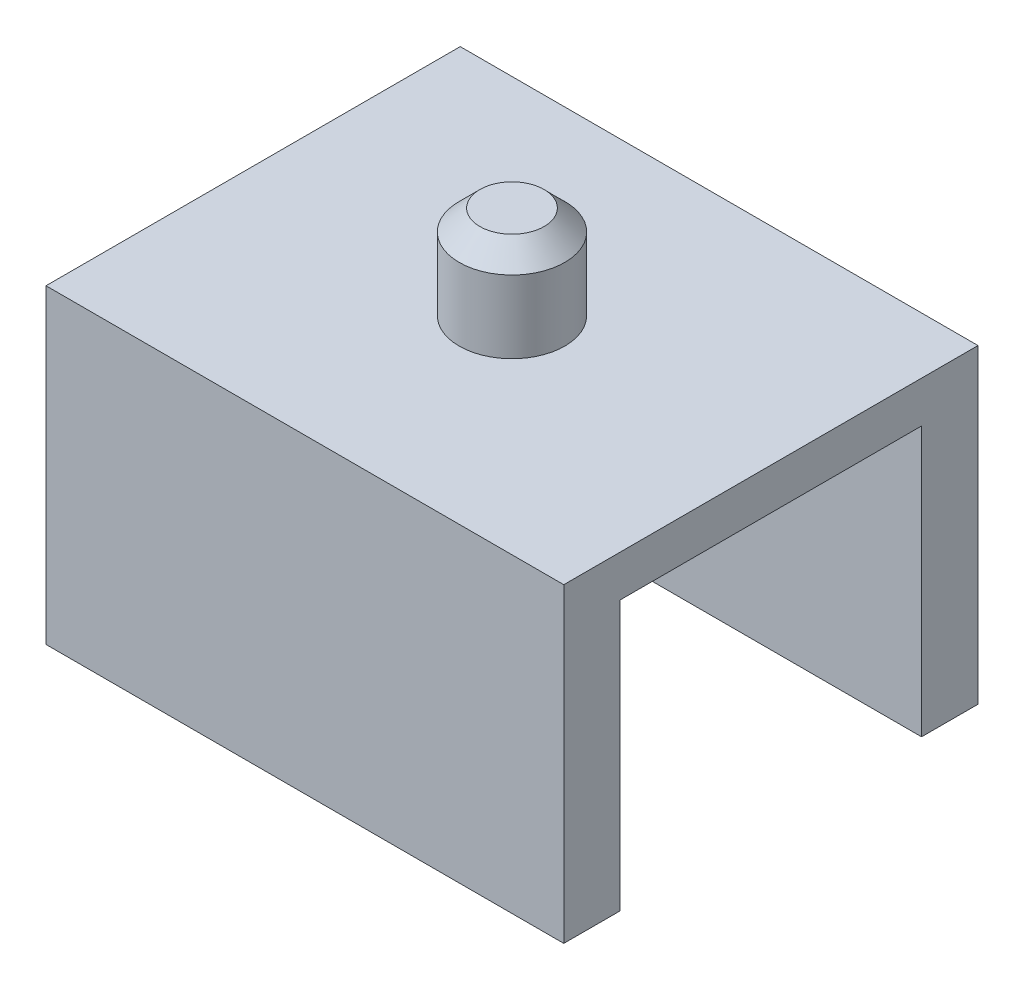
SolidWorks part; units mm, degrees
ref_plane "Top" through (0, 0, 0) normal (0, 0, 1) x (1, 0, 0)
ref_plane "Front" through (0, 0, 0) normal (0, 1, 0) x (1, 0, 0)
ref_plane "Right" through (0, 0, 0) normal (1, 0, 0) x (0, 0, -1)
sketch "Sketch1" plane through (0, 0, 0) normal (0, 0, 1) x (1, 0, 0)
  line L0 (0, 0) -> (0, 15)
  line L1 (0, 15) -> (25, 15)
  line L2 (25, 15) -> (25, 0)
  line L3 (25, 0) -> (0, 0)
  dimension "D1" = 25
  dimension "D2" = 15
extrude "Boss-Extrude1" add sketch "Sketch1" along normal blind 20
sketch "Sketch2" plane through (0, 0, 0) normal (0, -1, 0) x (1, 0, 0)
  line L0 (0, 2.725) -> (25, 2.725)
  line L1 (0, 20) -> (0, 0) construction
  line L2 (25, 20) -> (25, 0) construction
  line L3 (25, 2.725) -> (25, 17.275)
  line L4 (25, 17.275) -> (0, 17.275)
  line L5 (0, 17.275) -> (0, 2.725)
  line L6 (0, 0) -> (25, 0) construction
  dimension "D1" = 2.725
  dimension "D2" = 14.55
extrude "Cut-Extrude1" cut sketch "Sketch2" against normal blind 13
sketch "Sketch4" plane through (0, 15, 0) normal (0, 1, 0) x (1, 0, 0)
  line L0 (25, 0) -> (0, 0) construction
  line L2 (0, -20) -> (0, 0) construction
  circle A0 centre (12.5, -10) radius 2.55
  dimension "D2" = 12.5
  dimension "D3" = 5.1
  dimension "D1" = 10
extrude "Boss-Extrude2" add sketch "Sketch4" along normal blind 4.5
chamfer "Chamfer1" distance 1 angle 45 1 edges at (12.5, 19.5, 12.55)
sketch "Sketch5" plane through (0, 13, 0) normal (0, -1, 0) x (-1, 0, 0)
  line L0 (-25, 0) -> (0, 0) construction
  line L1 (0, -17.275) -> (0, -2.725) construction
  circle A0 centre (-12.5, -10) radius 1.25
  dimension "D3" = 2.5
  dimension "D1" = 10
  dimension "D2" = 12.5
extrude "Boss-Extrude3" add sketch "Sketch5" along normal blind 2.5
chamfer "Chamfer2" distance 1 angle 45 1 edges at (13.75, 10.5, 10)
